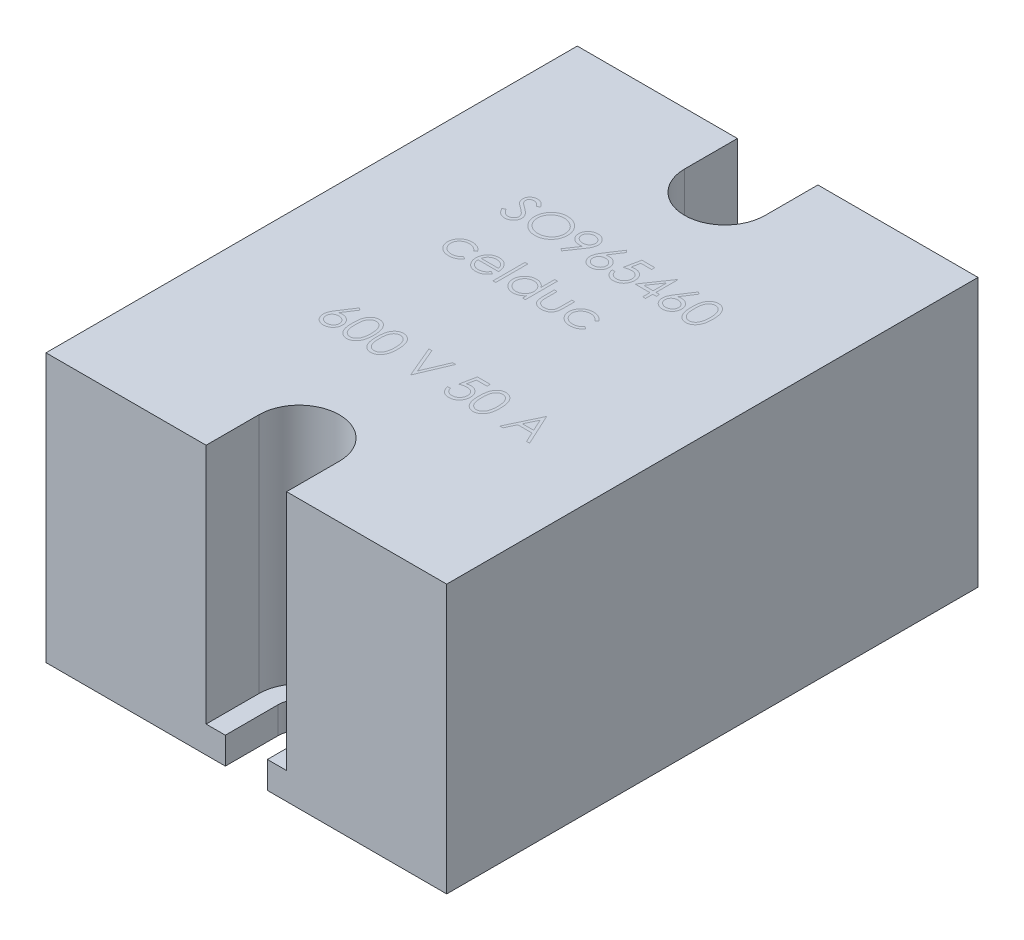
SolidWorks part; units mm, degrees
material "ABS"
ref_plane "Ground_Plane" through (0, 0, 0) normal (0, 0, 1) x (1, 0, 0)
ref_plane "VehicleCentre_Plane" through (0, 0, 0) normal (0, 1, 0) x (1, 0, 0)
ref_plane "FrontAxle_Plane" through (0, 0, 0) normal (1, 0, 0) x (0, 0, -1)
sketch "Sketch1" plane through (0, 0, 0) normal (0, 1, 0) x (1, 0, 0)
  line L1 (22.4, 29.7) -> (-22.4, 29.7)
  line L2 (22.4, 29.7) -> (22.4, -29.7)
  line L3 (22.4, -29.7) -> (-22.4, -29.7)
  line L4 (-22.4, 29.7) -> (-22.4, -29.7)
  line L5 (22.4, 29.7) -> (-22.4, -29.7) construction
  line L6 (22.4, -29.7) -> (-22.4, 29.7) construction
  point P0 (0, 0)
  dimension "D1" = 44.8
  dimension "D2" = 59.4
extrude "Boss-Extrude1" add sketch "Sketch1" along normal blind 30
sketch "Sketch3" plane through (0, 30, 0) normal (0, 1, 0) x (1, 0, 0)
  line L0 (-4.5, 23.8) -> (-4.5, 30.7)
  line L1 (-4.5, 30.7) -> (4.5, 30.7)
  line L2 (4.5, 30.7) -> (4.5, 23.8)
  line L3 (-4.5, -23.8) -> (-4.5, -30.7)
  line L4 (-4.5, -30.7) -> (4.5, -30.7)
  line L5 (4.5, -30.7) -> (4.5, -23.8)
  line L6 (22.4, 29.7) -> (-22.4, 29.7) construction
  arc A0 (-4.5, 23.8) -> (4.5, 23.8) centre (0, 23.8) ccw
  arc A1 (-4.5, -23.8) -> (4.5, -23.8) centre (0, -23.8) cw
  dimension "D1" = 9
  dimension "D2" = 1
  dimension "D3" = 23.8
  dimension "D4" = 47.6
extrude "Cut-Extrude1" cut sketch "Sketch3" against normal blind 27
sketch "Sketch4" plane through (0, 3, 0) normal (0, 1, 0) x (1, 0, 0)
  line L0 (-2.35, 23.8) -> (-2.35, 29.7)
  line L1 (4.5, 29.7) -> (-4.5, 29.7) construction
  line L2 (-2.35, 29.7) -> (2.35, 29.7)
  line L3 (2.35, 29.7) -> (2.35, 23.8)
  line L4 (-2.35, -23.8) -> (-2.35, -29.7)
  line L7 (-2.35, -29.7) -> (2.35, -29.7)
  line L8 (4.5, -29.7) -> (-4.5, -29.7) construction
  line L9 (2.35, -29.7) -> (2.35, -23.8)
  arc A0 (-2.35, 23.8) -> (2.35, 23.8) centre (0, 23.8) ccw
  arc A1 (2.35, -23.8) -> (-2.35, -23.8) centre (0, -23.8) ccw
  arc A2 (4.5, -23.8) -> (-4.5, -23.8) centre (0, -23.8) ccw construction
  arc A3 (-4.5, 23.8) -> (4.5, 23.8) centre (0, 23.8) ccw construction
  dimension "D1" = 4.7
extrude "Cut-Extrude2" cut sketch "Sketch4" against normal through all
sketch "Sketch2" plane through (0, 30, 0) normal (0, 1, 0) x (1, 0, 0)
  text T0 "SO965460\r\ncelduc\r\n\r\n600 V 50 A"
split line "Split Line1"
